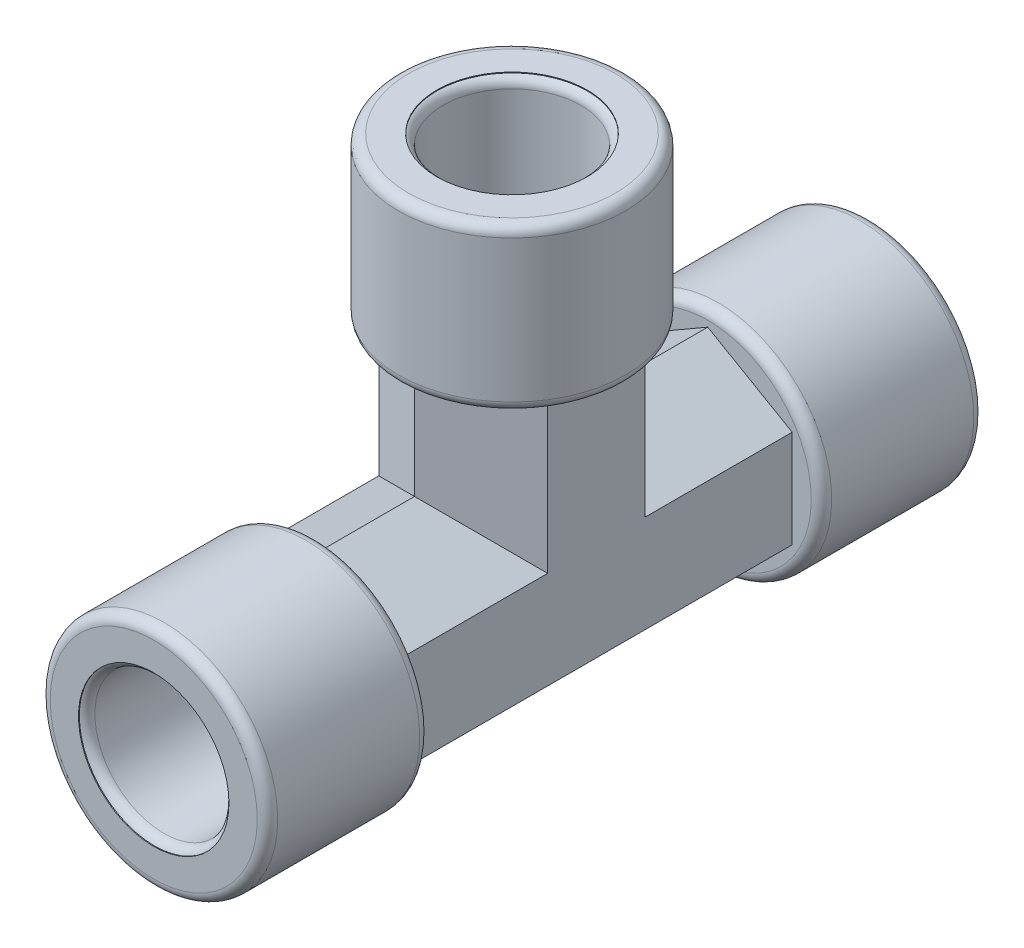
SolidWorks part; units mm, degrees
material "Latão"
ref_plane "Plano frontal" through (0, 0, 0) normal (0, 0, 1) x (1, 0, 0)
ref_plane "Plano superior" through (0, 0, 0) normal (0, 1, 0) x (1, 0, 0)
ref_plane "Plano direito" through (0, 0, 0) normal (1, 0, 0) x (0, 0, -1)
sketch "Esboço2" plane through (0, 0, 0) normal (0, 0, 1) x (1, 0, 0)
  line L1 (0, 4.7625) -> (-4.1244, 2.3812)
  line L2 (-4.1244, 2.3812) -> (-4.1244, -2.3813)
  line L3 (-4.1244, -2.3813) -> (0, -4.7625)
  line L4 (0, -4.7625) -> (4.1244, -2.3813)
  line L5 (4.1244, -2.3813) -> (4.1244, 2.3813)
  line L6 (4.1244, 2.3813) -> (0, 4.7625)
  circle A0 centre (0, 0) radius 4.7625 construction
  dimension "D1" = 9.525
extrude "Ressalto-extrusão1" add sketch "Esboço2" along normal blind 35
sketch "Esboço4" plane through (0, 0, 0) normal (0, 1, 0) x (1, 0, 0)
  line L0 (0, -35) -> (0, 0) construction
  line L1 (0, -12.7375) -> (-4.1244, -15.1187)
  line L2 (-4.1244, -15.1187) -> (-4.1244, -19.8812)
  line L3 (-4.1244, -19.8812) -> (0, -22.2625)
  line L4 (0, -22.2625) -> (4.1244, -19.8813)
  line L5 (4.1244, -19.8813) -> (4.1244, -15.1188)
  line L6 (4.1244, -15.1188) -> (0, -12.7375)
  circle A0 centre (0, -17.5) radius 4.7625 construction
  dimension "D1" = 9.525
extrude "Ressalto-extrusão3" add sketch "Esboço4" along normal blind 17.74
sketch "Esboço5" plane through (0, 0, 0) normal (0, 0, 1) x (1, 0, 0)
  circle A0 centre (0, 0) radius 2.3813
  dimension "D1" = 4.7625
extrude "Corte-extrusão1" cut sketch "Esboço5" along normal through all
sketch "Esboço6" plane through (0, 17.74, 0) normal (0, 1, 0) x (1, 0, 0)
  line L0 (-4.1244, -19.8812) -> (4.1244, -15.1188) construction
  line L1 (-4.1244, -15.1187) -> (4.1244, -19.8813) construction
  circle A0 centre (0, -17.5) radius 2.3813
  dimension "D1" = 4.7625
extrude "Corte-extrusão2" cut sketch "Esboço6" against normal up to next
sketch "Esboço7" plane through (0, 0, 0) normal (0, 0, -1) x (-1, 0, 0)
  circle A0 centre (0, 0) radius 3.3734
  dimension "D1" = 6.7469
extrude "Corte-extrusão3" cut sketch "Esboço7" against normal blind 6.35
sketch "Esboço8" plane through (0, 0, 35) normal (0, 0, 1) x (1, 0, 0)
  circle A0 centre (0, 0) radius 3.3734
  dimension "D1" = 6.7469
extrude "Corte-extrusão4" cut sketch "Esboço8" against normal blind 6.35
sketch "Esboço9" plane through (0, 17.74, 0) normal (0, 1, 0) x (1, 0, 0)
  circle A0 centre (0, -17.5) radius 3.3734
  dimension "D1" = 6.7469
extrude "Corte-extrusão5" cut sketch "Esboço9" against normal blind 6.35
fillet "Filete1" radius 0.5 1 edges at (-3.3734, 0, 0)
fillet "Filete2" radius 0.5 2 edges at (0, 17.74, 20.8734) (3.3734, 0, 35)
sketch "Esboço10" plane through (0, 0, 35) normal (0, 0, 1) x (1, 0, 0)
  circle A0 centre (0, 0) radius 5.5562
  circle A1 centre (0, 0) radius 3.675
  dimension "D1" = 11.1125
extrude "Ressalto-extrusão4" add sketch "Esboço10" against normal blind 7.9375
cosmetic thread "Representação de rosca1" parameters "D2"=9.6012
fillet "Filete3" radius 0.5 2 edges at (5.5562, 0, 27.0625) (5.5562, 0, 35)
sketch "Esboço11" plane through (0, 0, 0) normal (0, 0, -1) x (-1, 0, 0)
  circle A0 centre (0, 0) radius 3.675
  circle A1 centre (0, 0) radius 5.5562
  dimension "D1" = 11.1125
extrude "Ressalto-extrusão5" add sketch "Esboço11" against normal blind 7.9375
cosmetic thread "Representação de rosca2" parameters "D2"=9.6012
fillet "Filete4" radius 0.5 2 edges at (-5.5562, 0, 7.9375) (-5.5562, 0, 0)
sketch "Esboço12" plane through (0, 17.74, 0) normal (0, 1, 0) x (1, 0, 0)
  circle A0 centre (0, -17.5) radius 3.675
  circle A1 centre (0, -17.5) radius 5.5563
  dimension "D1" = 11.1125
extrude "Ressalto-extrusão6" add sketch "Esboço12" against normal blind 7.9375
cosmetic thread "Representação de rosca3" parameters "D2"=9.6012
fillet "Filete5" radius 0.5 2 edges at (0, 9.8025, 23.0563) (0, 17.74, 23.0563)
